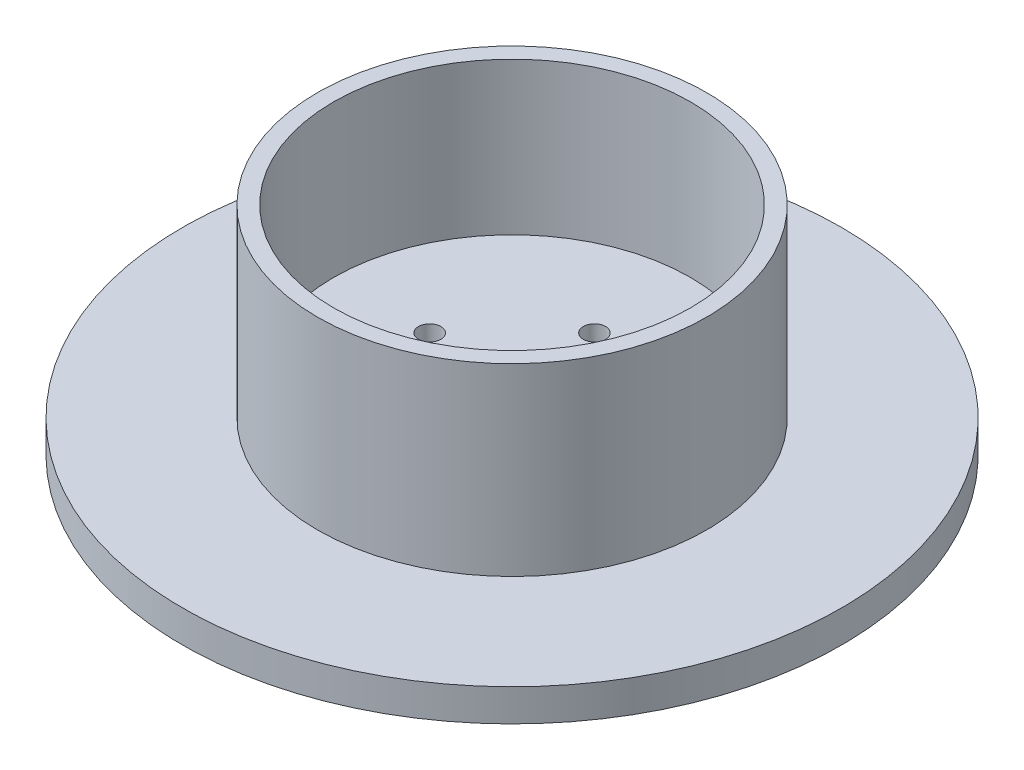
SolidWorks part; units mm, degrees
material "PLA"
ref_plane "Front Plane" through (0, 0, 0) normal (0, 0, 1) x (1, 0, 0)
ref_plane "Top Plane" through (0, 0, 0) normal (0, 1, 0) x (1, 0, 0)
ref_plane "Right Plane" through (0, 0, 0) normal (1, 0, 0) x (0, 0, -1)
sketch "Sketch1" plane through (0, 0, 0) normal (0, 1, 0) x (1, 0, 0)
  circle A0 centre (0, 0) radius 19.1875
  dimension "D1" = 38.375
extrude "Boss-Extrude1" add sketch "Sketch1" along normal blind 3.175
sketch "Sketch2" plane through (0, 3.175, 0) normal (0, 1, 0) x (1, 0, 0)
  circle A1 centre (0, 0) radius 19.1875 construction
  circle A2 centre (0, 0) radius 17.6
  circle A3 centre (0, 0) radius 17.6
  circle A4 centre (0, 0) radius 19.1875
  dimension "D1" = 1.5875
extrude "Boss-Extrude2" add sketch "Sketch2" along normal blind 15
sketch "Sketch3" plane through (0, 0, 0) normal (0, -1, 0) x (1, 0, 0)
  circle A0 centre (0, 0) radius 8.125 construction
  circle A1 centre (0, 8.125) radius 1.1
  circle A2 centre (8.125, 0) radius 1.1
  circle A3 centre (-8.125, 0) radius 1.1
  circle A4 centre (0, -8.125) radius 1.1
  dimension "D1" = 16.25
  dimension "D2" = 2.2
extrude "Cut-Extrude1" cut sketch "Sketch3" against normal through all
sketch "Sketch4" plane through (0, 0, 0) normal (0, -1, 0) x (1, 0, 0)
  circle A0 centre (0, 0) radius 32.5
  circle A1 centre (0, -8.125) radius 1.1 construction
  circle A2 centre (8.125, 0) radius 1.1 construction
  circle A3 centre (-8.125, 0) radius 1.1 construction
  circle A4 centre (0, 8.125) radius 1.1 construction
  circle A5 centre (0, -8.125) radius 1.1
  circle A6 centre (8.125, 0) radius 1.1
  circle A7 centre (-8.125, 0) radius 1.1
  circle A8 centre (0, 8.125) radius 1.1
  dimension "D1" = 65
extrude "Boss-Extrude3" add sketch "Sketch4" along normal blind 3.175
